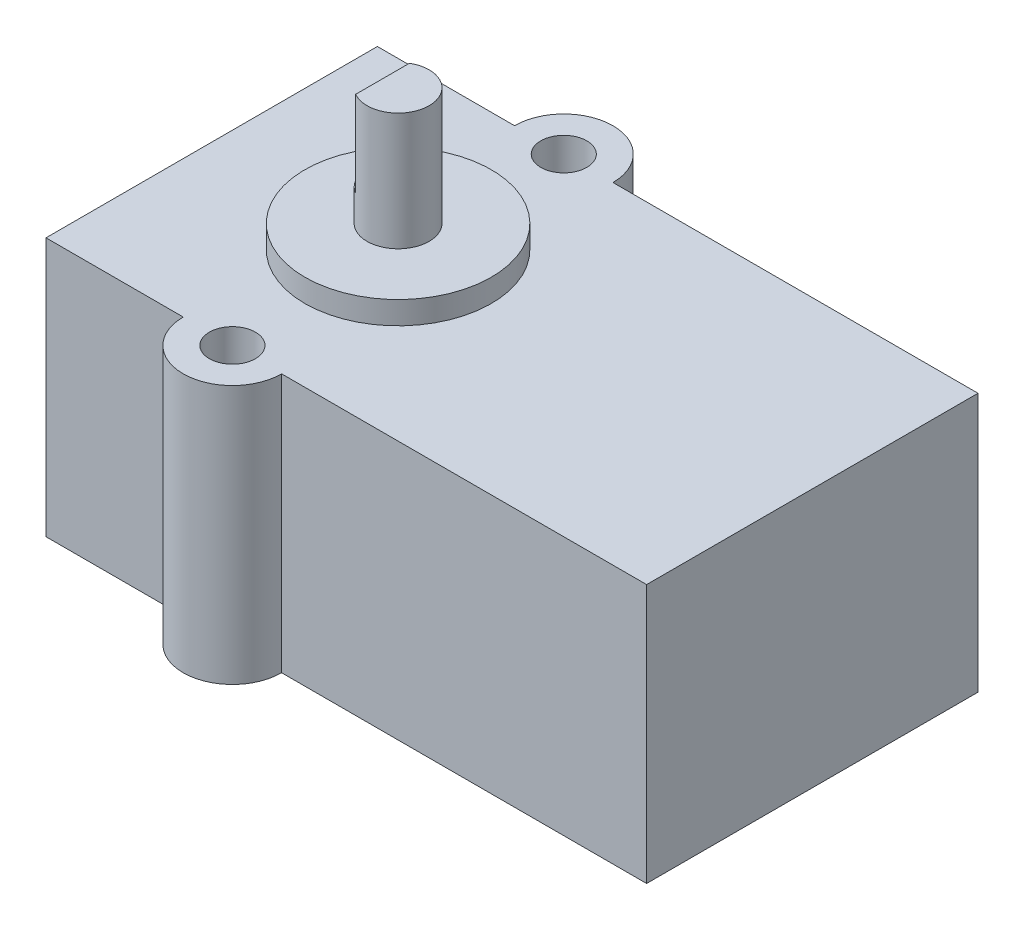
SolidWorks part; units mm, degrees
ref_plane "Front Plane" through (0, 0, 0) normal (0, 0, 1) x (1, 0, 0)
ref_plane "Top Plane" through (0, 0, 0) normal (0, 1, 0) x (1, 0, 0)
ref_plane "Right Plane" through (0, 0, 0) normal (1, 0, 0) x (0, 0, -1)
sketch "Sketch1" plane through (0, 0, 0) normal (0, 1, 0) x (1, 0, 0)
  line L0 (-5.75, -16) -> (-19, -16)
  line L1 (39, -16) -> (3.75, -16)
  line L2 (39, -16) -> (39, 16)
  line L3 (39, 16) -> (3.75, 16)
  line L4 (-19, -16) -> (-19, 16)
  line L5 (-5.75, 16) -> (-19, 16)
  line L6 (39, 0) -> (-19, 0) construction
  circle A0 centre (-1, -16) radius 2.225
  arc A1 (-5.75, -16) -> (3.75, -16) centre (-1, -16) ccw
  arc A2 (-5.75, 16) -> (3.75, 16) centre (-1, 16) cw
  circle A3 centre (-1, 16) radius 2.225
  point P0 (0, 0)
  dimension "D2" = 4.45
  dimension "D4" = 9.5
  dimension "D1" = 32
  dimension "D3" = 40
  dimension "D5" = 58
extrude "Boss-Extrude1" add sketch "Sketch1" along normal blind 25
sketch "Sketch2" plane through (0, 25, 0) normal (0, 1, 0) x (1, 0, 0)
  circle A0 centre (-1, 0) radius 9
extrude "Boss-Extrude2" add sketch "Sketch2" along normal blind 2.2
sketch "Sketch3" plane through (0, 27.2, 0) normal (0, 1, 0) x (1, 0, 0)
  circle A0 centre (-1, 0) radius 3
extrude "Boss-Extrude3" add sketch "Sketch3" along normal blind 11.35
sketch "Sketch4" plane through (0, 38.55, 0) normal (0, 1, 0) x (1, 0, 0)
  line L1 (-4, 3) -> (-2.5, 3)
  line L2 (-4, 3) -> (-4, -3)
  line L3 (-4, -3) -> (-2.5, -3)
  line L4 (-2.5, 3) -> (-2.5, -3)
  dimension "D1" = 1.5
extrude "Cut-Extrude1" cut sketch "Sketch4" against normal blind 8.3
